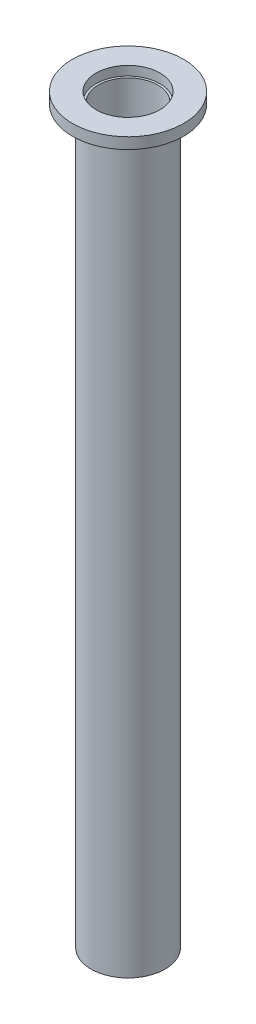
SolidWorks part; units mm, degrees
ref_plane "Front Plane" through (0, 0, 0) normal (0, 0, 1) x (1, 0, 0)
ref_plane "Top Plane" through (0, 0, 0) normal (0, 1, 0) x (1, 0, 0)
ref_plane "Right Plane" through (0, 0, 0) normal (1, 0, 0) x (0, 0, -1)
sketch "Reconstructed nominal axial profile" plane through (0, 0, 0) normal (0, 0, 1) x (1, 0, 0)
  line L0 (0, -500) -> (0, 50) construction
  line L1 (8.6, -78) -> (8.6, -80.5)
  line L2 (8.6, -80.5) -> (8, -80.5)
  line L3 (8, -80.5) -> (8, -278)
  line L4 (8, -278) -> (10, -278)
  line L5 (10, -278) -> (10, -82.3397)
  line L6 (10, -82.3397) -> (15, -81)
  line L7 (15, -81) -> (15, -78)
  line L8 (15, -78) -> (8.6, -78)
revolve "Native revolved geometry" add sketch "Reconstructed nominal axial profile" angle 360 about L0
